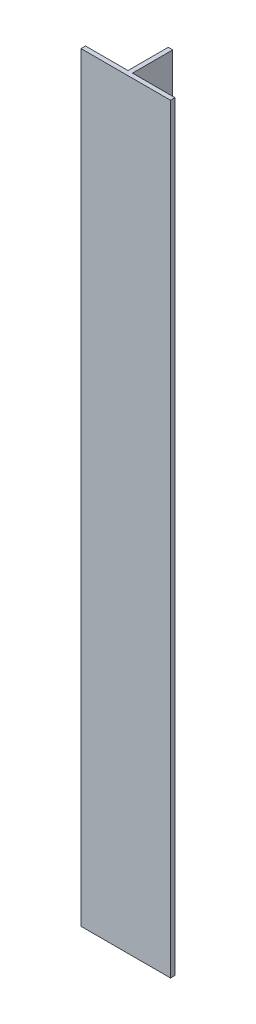
SolidWorks part; units mm, degrees
ref_plane "Front Plane" through (0, 0, 0) normal (0, 0, 1) x (1, 0, 0)
ref_plane "Top Plane" through (0, 0, 0) normal (0, 1, 0) x (1, 0, 0)
ref_plane "Right Plane" through (0, 0, 0) normal (1, 0, 0) x (0, 0, -1)
sketch "Sketch1" plane through (0, 0, 0) normal (0, 1, 0) x (1, 0, 0)
  line L0 (0, 5.3611) -> (0, 23.3611)
  line L1 (0, 23.3611) -> (2, 23.3611)
  line L2 (2, 23.3611) -> (2, 5.3611)
  line L3 (2, 5.3611) -> (21, 5.3611)
  line L4 (21, 5.3611) -> (21, 3.3611)
  line L5 (21, 3.3611) -> (-19, 3.3611)
  line L6 (-19, 3.3611) -> (-19, 5.3611)
  line L7 (-19, 5.3611) -> (0, 5.3611)
extrude "Boss-Extrude1" add sketch "Sketch1" along normal blind 340
